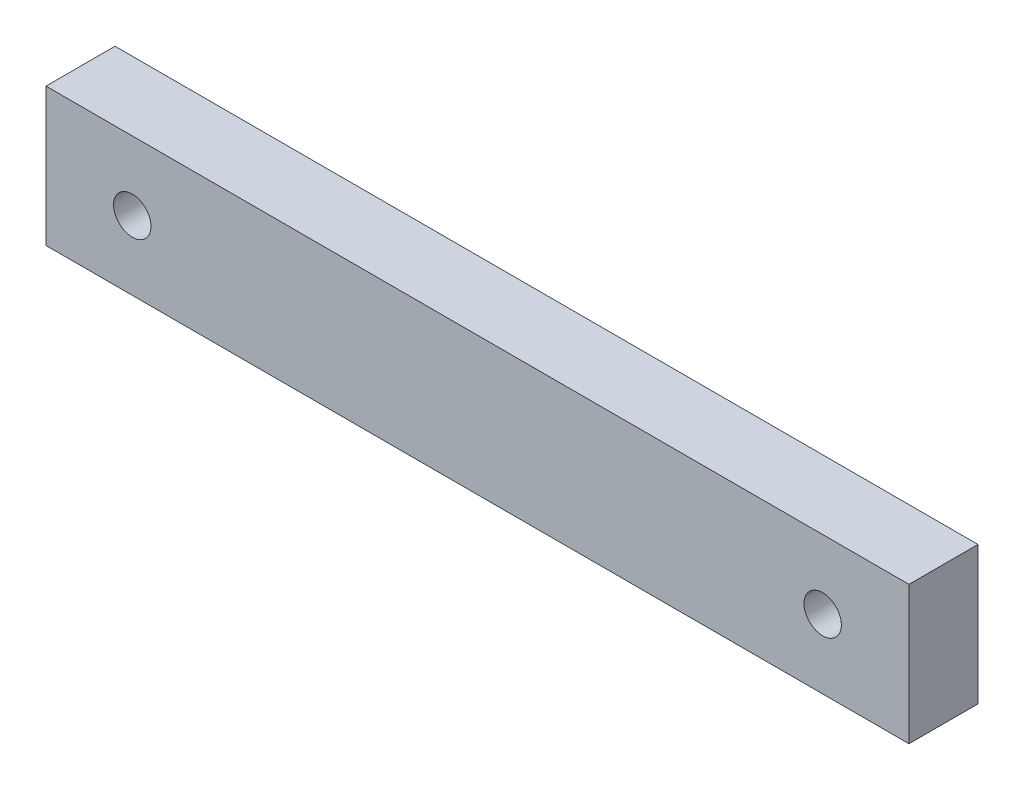
SolidWorks part; units mm, degrees
material "6063-T6"
ref_plane "Front Plane" through (0, 0, 0) normal (0, 0, 1) x (1, 0, 0)
ref_plane "Top Plane" through (0, 0, 0) normal (0, 1, 0) x (1, 0, 0)
ref_plane "Right Plane" through (0, 0, 0) normal (1, 0, 0) x (0, 0, -1)
sketch "Sketch2" plane through (0, 0, 0) normal (0, 0, 1) x (1, 0, 0)
  line L1 (-75, -12) -> (75, -12)
  line L2 (-75, -12) -> (-75, 12)
  line L3 (-75, 12) -> (75, 12)
  line L4 (75, -12) -> (75, 12)
  line L5 (-75, -12) -> (75, 12) construction
  line L6 (-75, 12) -> (75, -12) construction
  point P0 (0, 0)
  dimension "D1" = 150
  dimension "D2" = 24
extrude "Boss-Extrude1" add sketch "Sketch2" along normal mid plane 12
sketch "Sketch3" plane through (0, 0, 6) normal (0, 0, 1) x (1, 0, 0)
  line L4 (75, -12) -> (75, 12)
  line L5 (75, 12) -> (-75, 12)
  line L6 (-75, 12) -> (-75, -12)
  line L7 (-75, -12) -> (75, -12)
  line L8 (75, -12) -> (75, 12)
  line L9 (75, 12) -> (-75, 12)
  line L10 (-75, 12) -> (-75, -12)
  line L11 (-75, -12) -> (75, -12)
  circle A0 centre (-60, 0) radius 3.25
  circle A1 centre (60, 0) radius 3.25
  point P8 (0, 0)
  dimension "D6" = 6.5
  dimension "D2" = 15
  dimension "D3" = 15
  dimension "D4" = 12
  dimension "D5" = 12
  dimension "D1" = 0
extrude "Cut-Extrude1" cut sketch "Sketch3" against normal through all both and the other way through all contours A0 | A1
